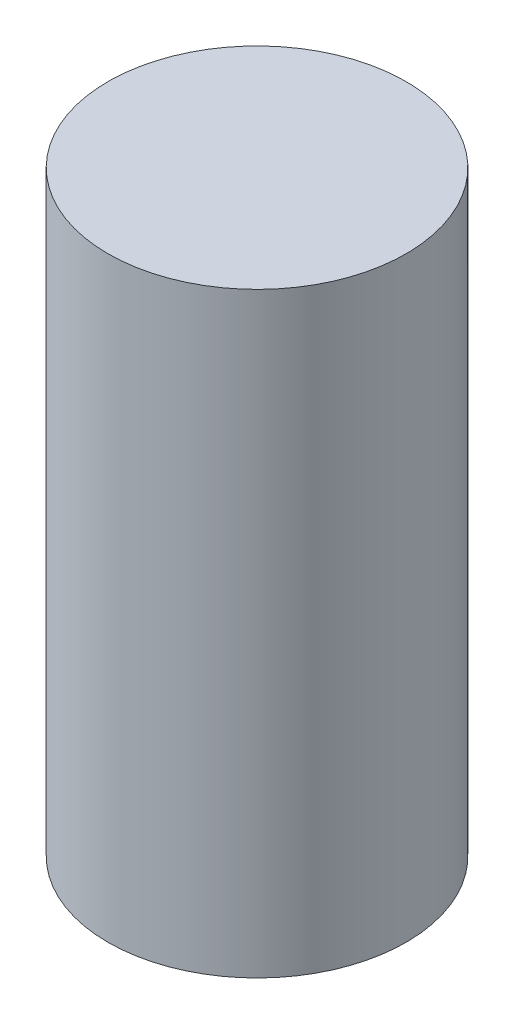
SolidWorks part; units mm, degrees
ref_plane "前视基准面" through (0, 0, 0) normal (0, 0, 1) x (1, 0, 0)
ref_plane "上视基准面" through (0, 0, 0) normal (0, 1, 0) x (1, 0, 0)
ref_plane "右视基准面" through (0, 0, 0) normal (1, 0, 0) x (0, 0, -1)
other "Configuration Table"
sketch "草图1" plane through (0, 0, 0) normal (0, 1, 0) x (1, 0, 0)
  circle A0 centre (0, 0) radius 15
  dimension "D1" = 30
extrude "凸台-拉伸1" add sketch "草图1" along normal blind 60
